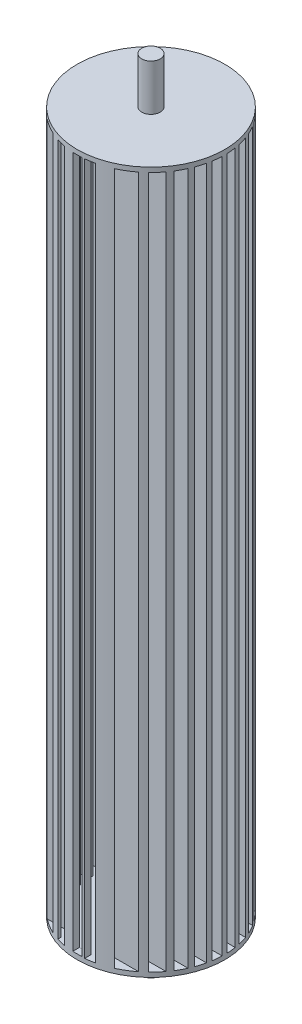
SolidWorks part; units mm, degrees
ref_plane "前视基准面" through (0, 0, 0) normal (0, 0, 1) x (1, 0, 0)
ref_plane "上视基准面" through (0, 0, 0) normal (0, 1, 0) x (1, 0, 0)
ref_plane "右视基准面" through (0, 0, 0) normal (1, 0, 0) x (0, 0, -1)
sketch "草图1" plane through (0, 0, 0) normal (0, 1, 0) x (1, 0, 0)
  circle A0 centre (0, 0) radius 80
  dimension "D1" = 160
extrude "凸台-拉伸1" add sketch "草图1" along normal blind 760
sketch "草图2" plane through (0, 760, 0) normal (0, 1, 0) x (1, 0, 0)
  circle A2 centre (0, 0) radius 65
extrude "切除-拉伸1" cut sketch "草图2" against normal offset from surface (750 mm away) 5 from offset 5 up to face at (0, 0, 80) offset against normal yes
ref_plane "基准面4" through (80, 0, 0) normal (1, 0, 0) x (0, 0, -1)
sketch "草图4" plane through (80, 0, 0) normal (1, 0, 0) x (0, 0, -1)
  line L0 (80, 760) -> (-80, 760) construction
  line L1 (-72.8154, 755) -> (-62.8154, 755)
  line L2 (-72.8154, 755) -> (-72.8154, 5)
  line L3 (-72.8154, 5) -> (-62.8154, 5)
  line L4 (-62.8154, 755) -> (-62.8154, 5)
  line L5 (-80, 0) -> (80, 0) construction
  line L6 (-57.8154, 755) -> (-47.8154, 755)
  line L7 (-57.8154, 755) -> (-57.8154, 5)
  line L8 (-57.8154, 5) -> (-47.8154, 5)
  line L9 (-47.8154, 755) -> (-47.8154, 5)
  line L10 (-42.8154, 755) -> (-32.8154, 755)
  line L11 (-42.8154, 755) -> (-42.8154, 5)
  line L12 (-42.8154, 5) -> (-32.8154, 5)
  line L13 (-32.8154, 755) -> (-32.8154, 5)
  line L14 (-12.8154, 755) -> (-2.8154, 755)
  line L15 (-12.8154, 755) -> (-12.8154, 5)
  line L16 (-12.8154, 5) -> (-2.8154, 5)
  line L17 (-2.8154, 755) -> (-2.8154, 5)
  line L18 (17.1846, 755) -> (27.1846, 755)
  line L19 (17.1846, 755) -> (17.1846, 5)
  line L20 (17.1846, 5) -> (27.1846, 5)
  line L21 (27.1846, 755) -> (27.1846, 5)
  line L22 (47.1846, 755) -> (57.1846, 755)
  line L23 (47.1846, 755) -> (47.1846, 5)
  line L24 (47.1846, 5) -> (57.1846, 5)
  line L25 (57.1846, 755) -> (57.1846, 5)
  line L26 (2.1846, 755) -> (12.1846, 755)
  line L27 (2.1846, 755) -> (2.1846, 5)
  line L28 (2.1846, 5) -> (12.1846, 5)
  line L29 (12.1846, 755) -> (12.1846, 5)
  line L30 (32.1846, 755) -> (42.1846, 755)
  line L31 (32.1846, 755) -> (32.1846, 5)
  line L32 (32.1846, 5) -> (42.1846, 5)
  line L33 (42.1846, 755) -> (42.1846, 5)
  line L34 (-27.8154, 755) -> (-17.8154, 755)
  line L35 (-27.8154, 755) -> (-27.8154, 5)
  line L36 (-27.8154, 5) -> (-17.8154, 5)
  line L37 (-17.8154, 755) -> (-17.8154, 5)
  line L38 (62.1846, 755) -> (72.1846, 755)
  line L39 (62.1846, 755) -> (62.1846, 4.1826)
  line L40 (62.1846, 4.1826) -> (72.1846, 4.1826)
  line L41 (72.1846, 755) -> (72.1846, 4.1826)
  point P36 (-52.8154, 755)
  point P41 (-37.8154, 755)
  dimension "D1" = 5
  dimension "D2" = 5
  dimension "D3" = 10
  dimension "D4" = 10
  dimension "D5" = 10
  dimension "D6" = 10
  dimension "D7" = 10
  dimension "D8" = 10
  dimension "D9" = 10
  dimension "D10" = 10
  dimension "D11" = 10
  dimension "D12" = 5
  dimension "D13" = 5
  dimension "D14" = 5
  dimension "D15" = 5
  dimension "D16" = 5
  dimension "D17" = 5
  dimension "D18" = 5
  dimension "D19" = 5
  dimension "D20" = 5
  dimension "D21" = 10
extrude "切除-拉伸5" cut sketch "草图4" against normal through all
ref_plane "基准面5" through (0, 0, 192.3529) normal (0, 0, 1) x (1, 0, 0)
sketch "草图5" plane through (0, 0, 192.3529) normal (0, 0, 1) x (1, 0, 0)
  line L0 (80, 760) -> (-80, 760) construction
  line L1 (-24.872, 755) -> (-14.872, 755)
  line L2 (-24.872, 755) -> (-24.872, 5)
  line L3 (-24.872, 5) -> (-14.872, 5)
  line L4 (-14.872, 755) -> (-14.872, 5)
  line L5 (-80, 0) -> (80, 0) construction
  line L6 (-4.7609, 755) -> (5.2391, 755)
  line L7 (-4.7609, 755) -> (-4.7609, 5.5706)
  line L8 (-4.7609, 5.5706) -> (5.2391, 5.5706)
  line L9 (5.2391, 755) -> (5.2391, 5.5706)
  line L10 (7.7403, 755) -> (17.7403, 755)
  line L11 (7.7403, 755) -> (7.7403, 5)
  line L12 (7.7403, 5) -> (17.7403, 5)
  line L13 (17.7403, 755) -> (17.7403, 5)
  point P16 (0, -335)
  point P17 (17.7403, -335)
  dimension "D1" = 5
  dimension "D2" = 5
  dimension "D3" = 10
  dimension "D4" = 10
  dimension "D5" = 10
extrude "切除-拉伸6" cut sketch "草图5" against normal blind 1100
sketch "草图6" plane through (0, 760, 0) normal (0, 1, 0) x (1, 0, 0)
  circle A0 centre (0, 0) radius 10
  dimension "D1" = 20
extrude "凸台-拉伸2" add sketch "草图6" along normal blind 50
sketch "草图7" plane through (0, 0, 0) normal (0, -1, 0) x (1, 0, 0)
  circle A0 centre (0, 0) radius 10
  point P1 (0, 0)
extrude "凸台-拉伸3" add sketch "草图7" along normal blind 50
